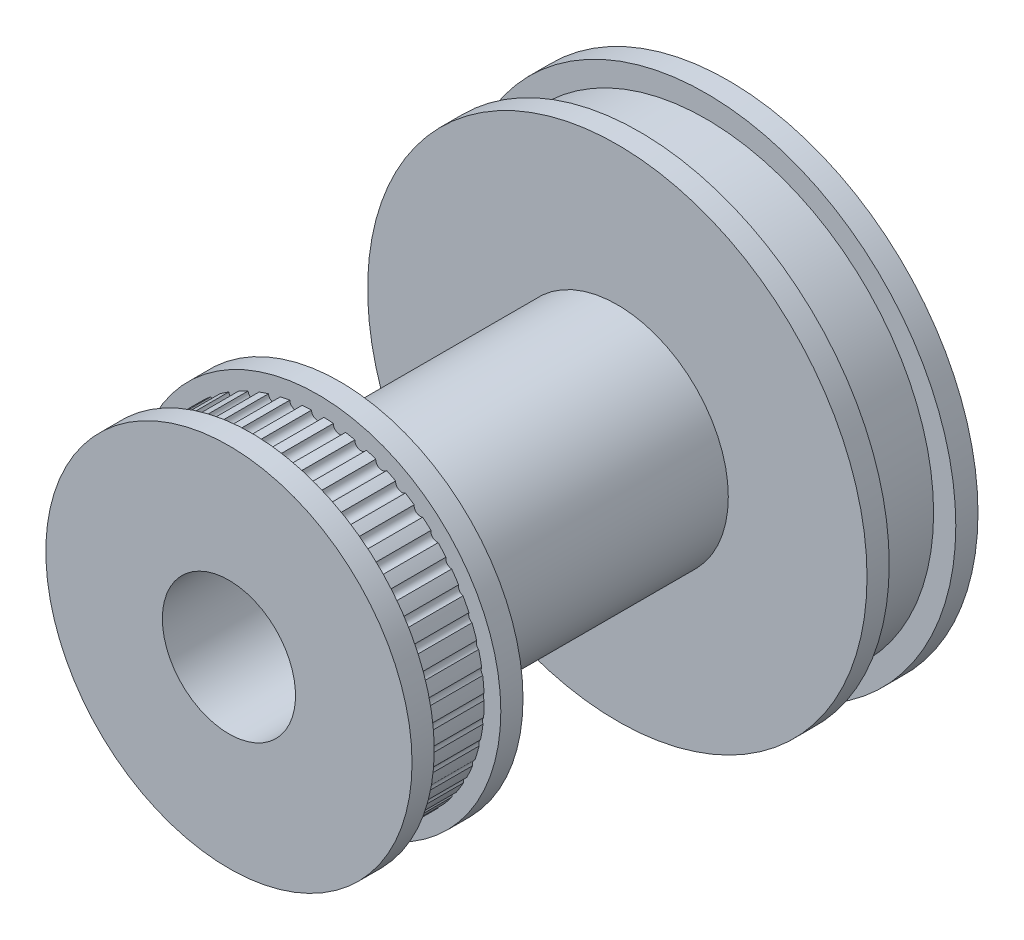
SolidWorks part; units mm, degrees
ref_plane "Vorne" through (0, 0, 0) normal (0, 0, 1) x (1, 0, 0)
ref_plane "Oben" through (0, 0, 0) normal (0, 1, 0) x (1, 0, 0)
ref_plane "Rechts" through (0, 0, 0) normal (1, 0, 0) x (0, 0, -1)
ref_plane "E_Boden" through (0, 1, 0) normal (0, 1, 0) x (1, 0, 0)
sketch "Skizze1" plane through (0, 0, 0) normal (0, 0, 1) x (1, 0, 0)
  line L0 (0, -37.3227) -> (0, 48.2798) construction
  line L1 (-67.1123, 0) -> (65.2861, 0) construction
  circle A0 centre (0, 0) radius 22.5
  dimension "D1" = 45
extrude "Seite1" add sketch "Skizze1" along normal blind 2
sketch "Skizze2" plane through (0, 0, 0) normal (0, 0, 1) x (1, 0, 0)
  circle A0 centre (0, 0) radius 20.5
  dimension "D1" = 41
extrude "Lauffläche" add sketch "Skizze2" along normal blind 8
sketch "Skizze5" plane through (0, 0, 8) normal (0, 0, 1) x (1, 0, 0)
  circle A0 centre (0, 0) radius 22.5
extrude "Seite 2" add sketch "Skizze5" along normal blind 2
sketch "Skizze7" plane through (0, 0, 0) normal (0, 0, 1) x (1, 0, 0)
  circle A0 centre (0, 0) radius 2.5
  dimension "D1" = 5
extrude "Bohrung" cut sketch "Skizze7" along normal blind 100 and the other way through all
sketch "Skizze9" plane through (0, 0, 10) normal (0, 0, 1) x (1, 0, 0)
  circle A0 centre (0, 0) radius 10
  dimension "D1" = 20
extrude "Zapfen" add sketch "Skizze9" along normal blind 25
sketch "Skizze10" plane through (0, 0, 35) normal (0, 0, 1) x (1, 0, 0)
  line L0 (0, 16.5) -> (0, -16.5) construction
  line L1 (-16.5, 0) -> (16.5, 0) construction
  circle A0 centre (0, 0) radius 16.5
  point P10 (0, 0)
  dimension "D1" = 33
extrude "Seitenteil3" add sketch "Skizze10" along normal blind 2
sketch "Skizze12" plane through (0, 0, 37) normal (0, 0, 1) x (1, 0, 0)
  circle A0 centre (0, 0) radius 15
  dimension "D1" = 30
extrude "Zahnfläche" add sketch "Skizze12" along normal blind 6
sketch "Skizze14" plane through (0, 0, 43) normal (0, 0, 1) x (1, 0, 0)
  line L0 (0, 15) -> (0, -15) construction
  line L1 (-15, 0) -> (15, 0) construction
  circle A0 centre (0, 0) radius 15 construction
  circle A1 centre (0, 0) radius 15 construction
  circle A2 centre (0, 15) radius 0.56
  circle A4 centre (1.9666, 14.9289) radius 0.56
  circle A5 centre (3.907, 14.6016) radius 0.56
  circle A6 centre (5.7881, 14.0239) radius 0.56
  circle A7 centre (7.5778, 13.2057) radius 0.56
  circle A8 centre (9.2453, 12.1608) radius 0.56
  circle A9 centre (10.7622, 10.9072) radius 0.56
  circle A10 centre (12.1024, 9.4663) radius 0.56
  circle A11 centre (13.2432, 7.8628) radius 0.56
  circle A12 centre (14.1648, 6.1242) radius 0.56
  circle A13 centre (14.8517, 4.2801) radius 0.56
  circle A14 centre (15.2919, 2.3621) radius 0.56
  circle A15 centre (15.4781, 0.4031) radius 0.56
  circle A16 centre (15.407, -1.5635) radius 0.56
  circle A17 centre (15.0797, -3.5039) radius 0.56
  circle A18 centre (14.502, -5.385) radius 0.56
  circle A19 centre (13.6837, -7.1747) radius 0.56
  circle A20 centre (12.6389, -8.8422) radius 0.56
  circle A21 centre (11.3853, -10.3591) radius 0.56
  circle A22 centre (9.9444, -11.6993) radius 0.56
  circle A23 centre (8.3409, -12.8401) radius 0.56
  circle A24 centre (6.6023, -13.7617) radius 0.56
  circle A25 centre (4.7582, -14.4486) radius 0.56
  circle A26 centre (2.8402, -14.8888) radius 0.56
  circle A27 centre (0.8812, -15.075) radius 0.56
  circle A28 centre (-1.0854, -15.0039) radius 0.56
  circle A29 centre (-3.0258, -14.6766) radius 0.56
  circle A30 centre (-4.907, -14.0989) radius 0.56
  circle A31 centre (-6.6966, -13.2807) radius 0.56
  circle A32 centre (-8.3641, -12.2358) radius 0.56
  circle A33 centre (-9.881, -10.9822) radius 0.56
  circle A34 centre (-11.2212, -9.5413) radius 0.56
  circle A35 centre (-12.362, -7.9378) radius 0.56
  circle A36 centre (-13.2836, -6.1992) radius 0.56
  circle A37 centre (-13.9705, -4.3551) radius 0.56
  circle A38 centre (-14.4108, -2.4371) radius 0.56
  circle A39 centre (-14.5969, -0.4781) radius 0.56
  circle A40 centre (-14.5258, 1.4885) radius 0.56
  circle A41 centre (-14.1986, 3.4289) radius 0.56
  circle A42 centre (-13.6209, 5.31) radius 0.56
  circle A43 centre (-12.8026, 7.0997) radius 0.56
  circle A44 centre (-11.7577, 8.7672) radius 0.56
  circle A45 centre (-10.5041, 10.2841) radius 0.56
  circle A46 centre (-9.0632, 11.6243) radius 0.56
  circle A47 centre (-7.4597, 12.7651) radius 0.56
  circle A48 centre (-5.7211, 13.6867) radius 0.56
  circle A49 centre (-3.877, 14.3736) radius 0.56
  circle A50 centre (-1.959, 14.8138) radius 0.56
  point P85 (0.4406, -0.0375)
  dimension "D1" = 1.12
  dimension "D2" = 48
extrude "Riemenprofil" cut sketch "Skizze14" against normal up to surface (6 mm away) up to face at (15, 0, 37)
sketch "Skizze13" plane through (0, 0, 43) normal (0, 0, 1) x (1, 0, 0)
  circle A0 centre (0, 0) radius 16.5
  dimension "D1" = 33
extrude "Seitenteil4" add sketch "Skizze13" along normal blind 2
hole_wizard "Ø12.0 (12) Durchmesser Bohrung1" positions "Skizze15" profile "Skizze17" hole size "Ø12.0" standard "DIN" end condition through all
sketch "Skizze15" plane through (0, 0, 0) normal (0, 0, -1) x (-1, 0, 0)
  point P0 (0, 0)
sketch "Skizze17" plane through (0, 0, 0) normal (1, 0, 0) x (0, 1, 0)
  line L0 (0, 0) -> (0, 45)
  line L1 (0, 45) -> (6, 45)
  line L2 (6, 45) -> (6, 0)
  line L5 (6, 0) -> (0, 0)
  line L11 (0, -6.35) -> (0, 107.95) construction
  dimension "Bohrerdurchmesser" = 12
  dimension "Bohrungstiefe" = 45
